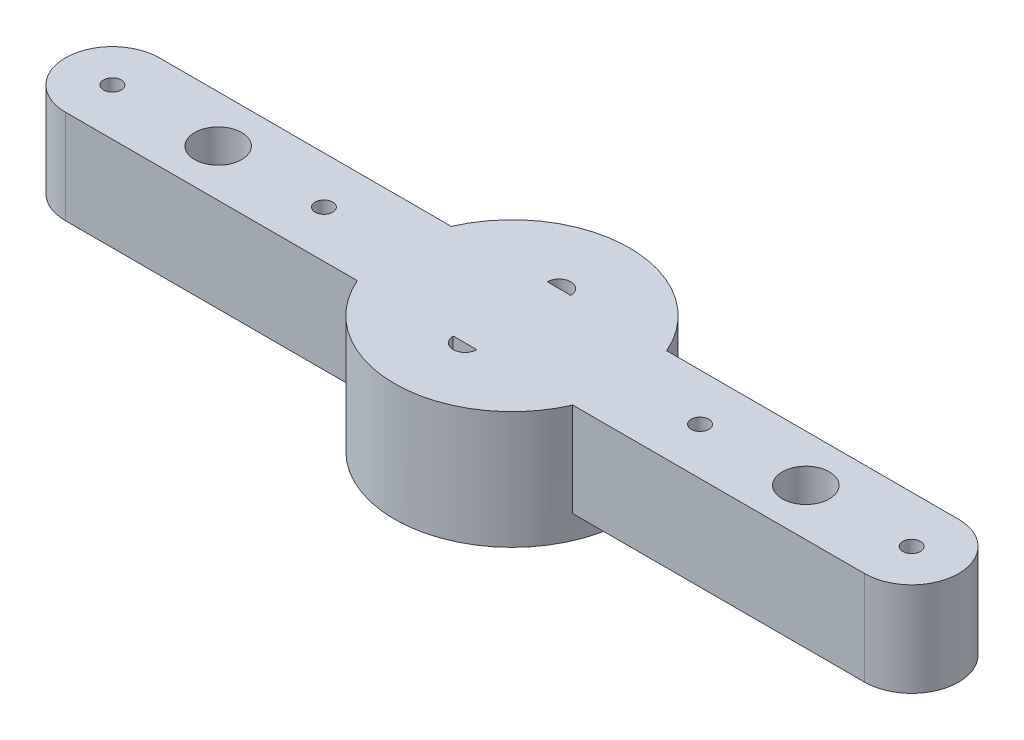
SolidWorks part; units mm, degrees
ref_plane "前基準面" through (0, 0, 0) normal (0, 0, 1) x (1, 0, 0)
ref_plane "上基準面" through (0, 0, 0) normal (0, 1, 0) x (1, 0, 0)
ref_plane "右基準面" through (0, 0, 0) normal (1, 0, 0) x (0, 0, -1)
sketch "草圖1" plane through (0, 0, 0) normal (0, 1, 0) x (1, 0, 0)
  line L0 (-25, 0) -> (25, 0) construction
  line L1 (-0.414, -4) -> (25, -4)
  line L2 (-0.414, 4) -> (25, 4)
  line L3 (34, 0) -> (-34, 0) construction
  line L4 (-34, 4) -> (-0.414, 4)
  line L5 (-34, -4) -> (-0.414, -4)
  line L6 (25, 4) -> (34, 4)
  line L7 (34, -4) -> (25, -4)
  circle A0 centre (34, 0) radius 0.75
  circle A1 centre (-34, 0) radius 0.75
  circle A2 centre (-25, 0) radius 2
  circle A3 centre (25, 0) radius 2
  arc A4 (-34, 4) -> (-34, -4) centre (-34, 0) ccw
  arc A5 (34, 4) -> (34, -4) centre (34, 0) cw
  circle A7 centre (-16, 0) radius 0.75
  circle A8 centre (16, 0) radius 0.75
  dimension "D2" = 4
  dimension "D3" = 9
  dimension "D4" = 1.5
  dimension "D1" = 50
  dimension "D5" = 8
  dimension "D11" = 9
  dimension "D12" = 9
extrude "填料-伸長1" add sketch "草圖1" along normal blind 8
sketch "草圖2" plane through (0, 8, 0) normal (0, 1, 0) x (-1, 0, 0)
  line L0 (-34, -4) -> (34, -4) construction
  line L1 (34, 4) -> (-34, 4) construction
  circle A0 centre (0, 0) radius 10
  circle A1 centre (0, -4) radius 1
  circle A2 centre (0, 4) radius 1
  dimension "D1" = 20
  dimension "D2" = 2
  dimension "D3" = 2
extrude "填料-伸長2" add sketch "草圖2" against normal blind 10
